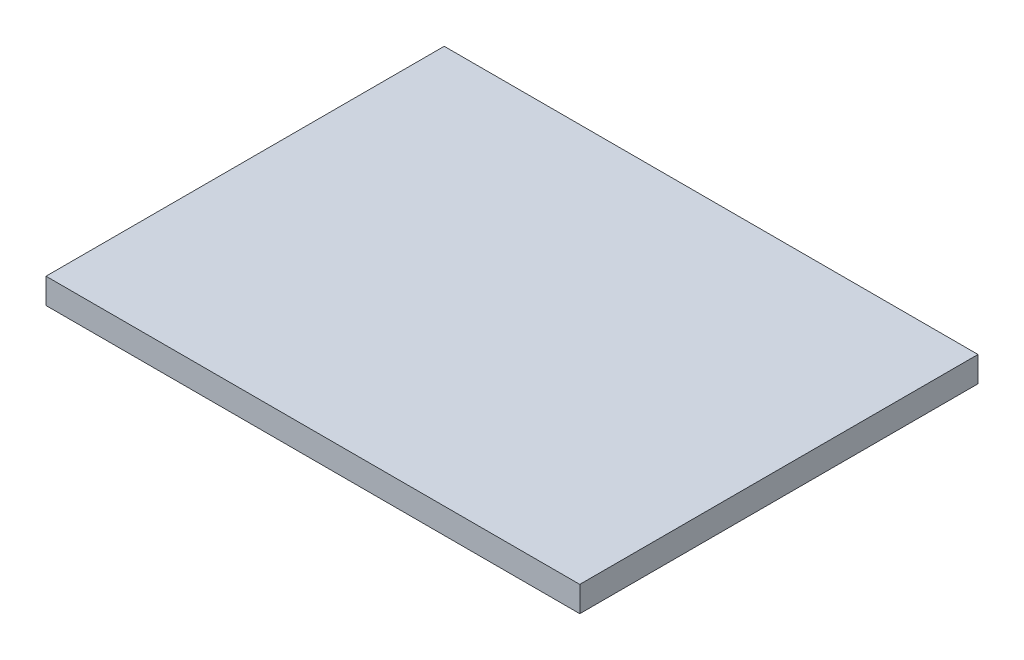
SolidWorks part; units mm, degrees
ref_plane "Front Plane" through (0, 0, 0) normal (0, 0, 1) x (1, 0, 0)
ref_plane "Top Plane" through (0, 0, 0) normal (0, 1, 0) x (1, 0, 0)
ref_plane "Right Plane" through (0, 0, 0) normal (1, 0, 0) x (0, 0, -1)
sketch "Sketch1" plane through (0, 0, 0) normal (0, 1, 0) x (1, 0, 0)
  line L1 (-315, 235) -> (315, 235)
  line L2 (-315, 235) -> (-315, -235)
  line L3 (-315, -235) -> (315, -235)
  line L4 (315, 235) -> (315, -235)
  line L5 (-315, 235) -> (315, -235) construction
  line L6 (-315, -235) -> (315, 235) construction
  point P0 (0, 0)
  dimension "D1" = 630
  dimension "D2" = 470
extrude "Boss-Extrude1" add sketch "Sketch1" along normal blind 30
